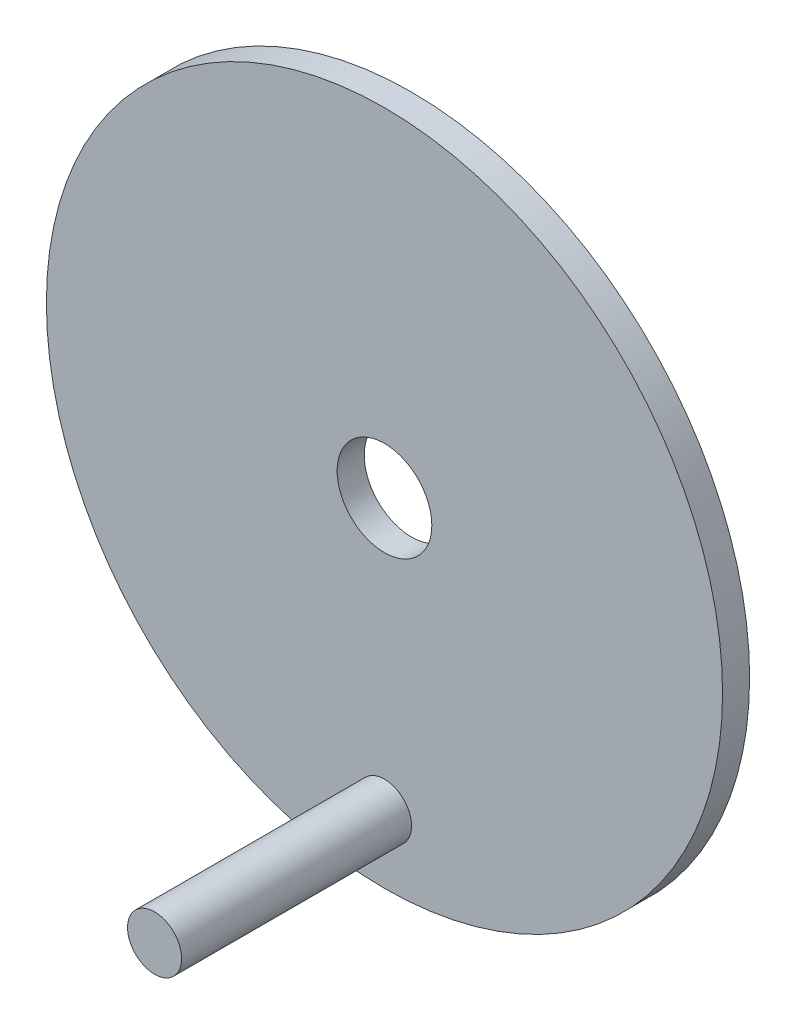
SolidWorks part; units mm, degrees
material "AISI 1020"
ref_plane "Ön Düzlem" through (0, 0, 0) normal (0, 0, 1) x (1, 0, 0)
ref_plane "Üst Düzlem" through (0, 0, 0) normal (0, 1, 0) x (1, 0, 0)
ref_plane "Sağ Düzlem" through (0, 0, 0) normal (1, 0, 0) x (0, 0, -1)
sketch "Çizim1" plane through (0, 0, 0) normal (0, 0, 1) x (1, 0, 0)
  circle A0 centre (0, 0) radius 250
  circle A1 centre (0, 0) radius 35
  dimension "D1" = 500
  dimension "D2" = 70
extrude "Yükseklik-Ekstrüzyon1" add sketch "Çizim1" along normal blind 20
sketch "Çizim2" plane through (0, 0, 20) normal (0, 0, 1) x (1, 0, 0)
  line L0 (0, 0) -> (0, -200) construction
  circle A0 centre (0, -200) radius 20
  dimension "D2" = 40
  dimension "D1" = 200
extrude "Yükseklik-Ekstrüzyon2" add sketch "Çizim2" along normal blind 170
